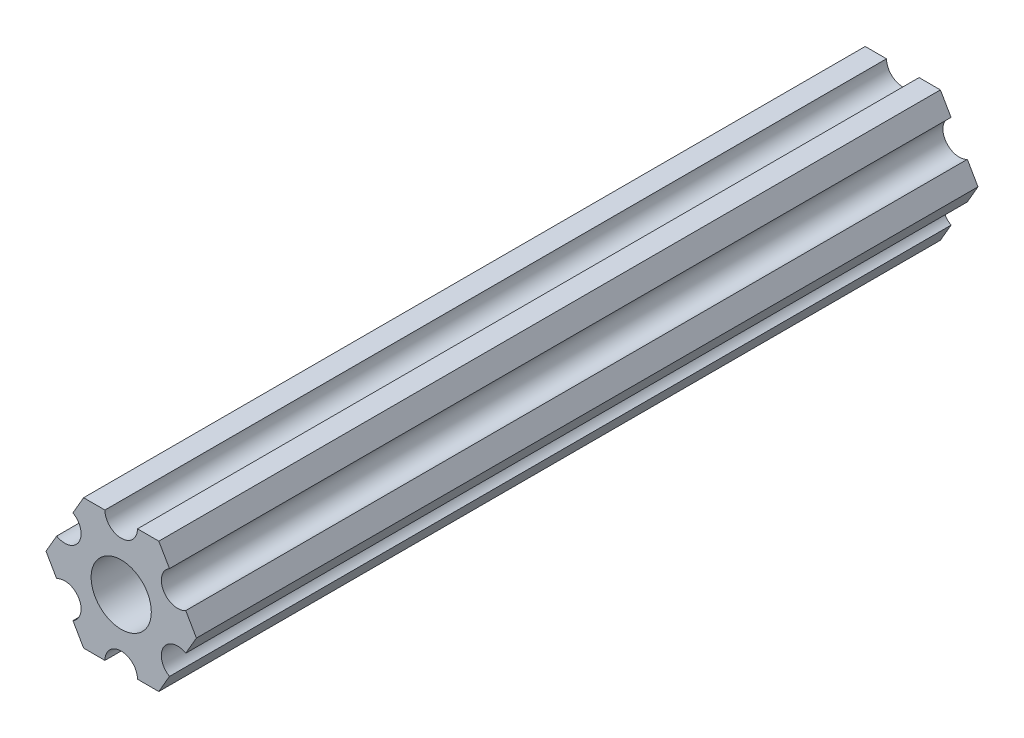
SolidWorks part; units mm, degrees
ref_plane "Front Plane" through (0, 0, 0) normal (0, 0, 1) x (1, 0, 0)
ref_plane "Top Plane" through (0, 0, 0) normal (0, 1, 0) x (1, 0, 0)
ref_plane "Right Plane" through (0, 0, 0) normal (1, 0, 0) x (0, 0, -1)
ref_plane "Plane1" through (0, 0, 0) normal (0, 0, -1) x (-1, 0, 0)
sketch "Sketch1" plane through (0, 0, 0) normal (0, 0, -1) x (-1, 0, 0)
  line L0 (-4.7055, -4.5498) -> (-3.6662, -6.35)
  line L1 (-3.6662, -6.35) -> (-1.5875, -6.35)
  line L2 (1.5875, -6.35) -> (3.6662, -6.35)
  line L3 (3.6662, -6.35) -> (4.7055, -4.5498)
  line L4 (6.293, -1.8002) -> (7.3323, 0)
  line L5 (7.3323, 0) -> (6.293, 1.8002)
  line L6 (4.7055, 4.5498) -> (3.6662, 6.35)
  line L7 (3.6662, 6.35) -> (1.5875, 6.35)
  line L8 (-1.5875, 6.35) -> (-3.6662, 6.35)
  line L9 (-3.6662, 6.35) -> (-4.7055, 4.5498)
  line L10 (-6.293, 1.8002) -> (-7.3323, 0)
  line L11 (-7.3323, 0) -> (-6.293, -1.8002)
  circle A0 centre (0, 0) radius 2.9337
  arc A1 (-6.293, -1.8002) -> (-4.7055, -4.5498) centre (-5.4993, -3.175) cw
  arc A2 (-1.5875, -6.35) -> (1.5875, -6.35) centre (0, -6.35) cw
  arc A3 (4.7055, -4.5498) -> (6.293, -1.8002) centre (5.4993, -3.175) cw
  arc A4 (6.293, 1.8002) -> (4.7055, 4.5498) centre (5.4993, 3.175) cw
  arc A5 (1.5875, 6.35) -> (-1.5875, 6.35) centre (0, 6.35) cw
  arc A6 (-4.7055, 4.5498) -> (-6.293, 1.8002) centre (-5.4993, 3.175) cw
extrude "Boss-Extrude1" add sketch "Sketch1" along normal blind 76.2
